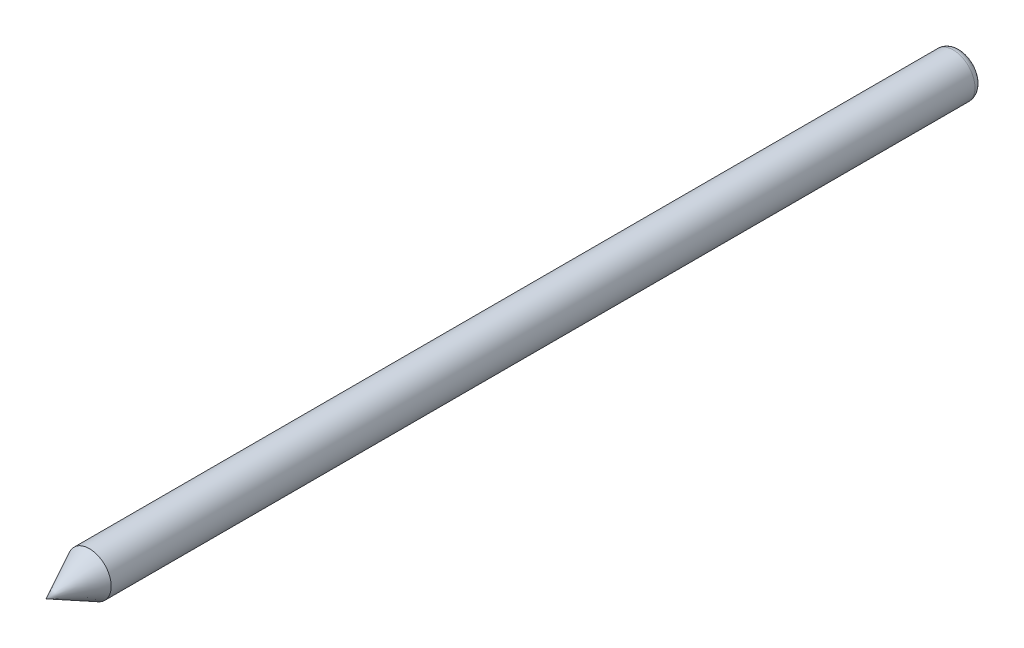
SolidWorks part; units mm, degrees
material "Custom Plastic"
ref_plane "Front Plane" through (0, 0, 0) normal (0, 0, 1) x (1, 0, 0)
ref_plane "Top Plane" through (0, 0, 0) normal (0, 1, 0) x (1, 0, 0)
ref_plane "Right Plane" through (0, 0, 0) normal (1, 0, 0) x (0, 0, -1)
sketch "Sketch1" plane through (0, 0, 0) normal (0, 0, 1) x (1, 0, 0)
  circle A0 centre (0, 0) radius 3
  dimension "D1" = 6
extrude "Boss-Extrude1" add sketch "Sketch1" along normal blind 120
ref_axis "Axis1" through (0, 0, 147.9065) along (0, 0, -1)
sketch "Sketch4" plane through (0, 0, 0) normal (0, 1, 0) x (1, 0, 0)
  line L0 (3, -120) -> (0, -125.9829)
  line L1 (-3, -120) -> (3, -120) construction
  line L2 (0, -3.3) -> (0, 3.3) construction
  line L3 (0, -147.9065) -> (0, -50) construction
  line L4 (0, -125.9829) -> (0, -120)
  line L6 (0, -120) -> (3, -120)
revolve "Revolve2" add sketch "Sketch4" angle 360 about axis through (0, 0, 147.9065) along (0, 0, -1)
fillet "Fillet1" radius 1 1 edges at (3, 0, 0)
